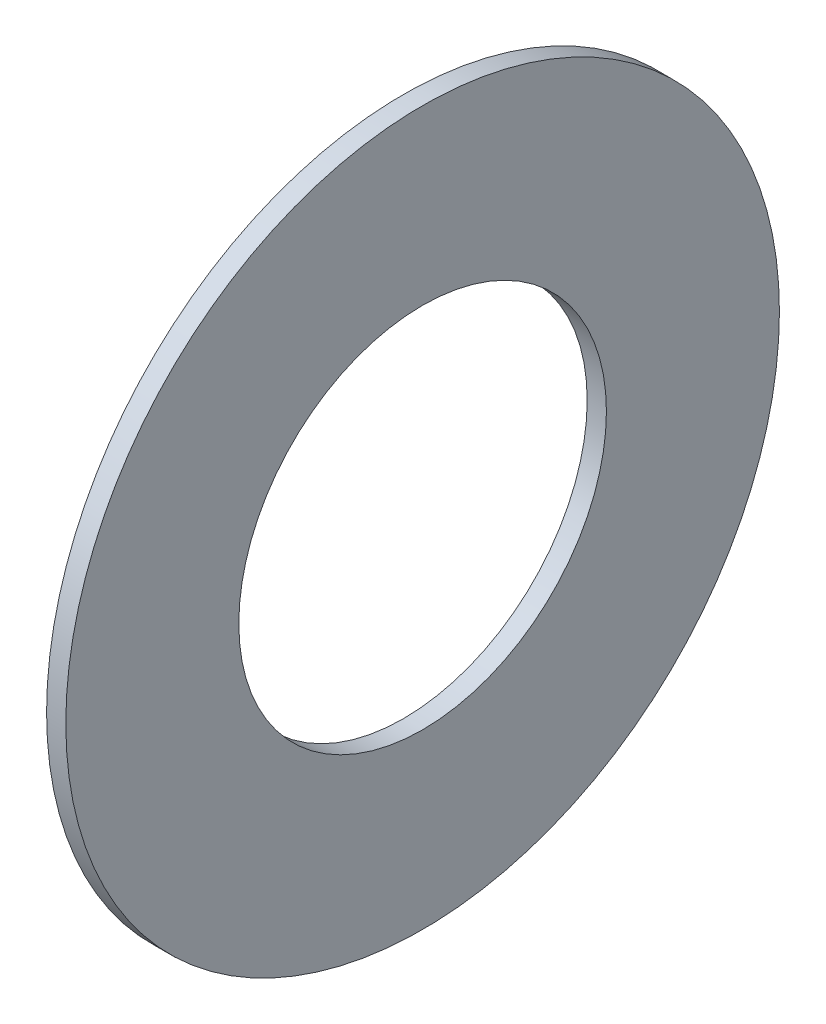
SolidWorks part; units mm, degrees
material "ﾎﾟﾘｵｷｼﾒﾁﾚﾝ(POM)ｱｾﾀｰﾙ共重合体"
ref_plane "正面" through (0, 0, 0) normal (0, 0, 1) x (1, 0, 0)
ref_plane "平面" through (0, 0, 0) normal (0, 1, 0) x (1, 0, 0)
ref_plane "右側面" through (0, 0, 0) normal (1, 0, 0) x (0, 0, -1)
sketch "ｽｹｯﾁ2" plane through (0, 0, 0) normal (0, 0, 1) x (1, 0, 0)
  line L0 (0, 0) -> (50000, 0) construction
  line L1 (-0.4, 14.85) -> (-0.4, 7.65)
  line L2 (-0.4, 7.65) -> (0.4, 7.65)
  line L3 (0.4, 7.65) -> (0.4, 14.85)
  line L4 (0.4, 14.85) -> (-0.4, 14.85)
  point P7 (0, 7.65)
  dimension "D1" = 0.8
  dimension "D2" = 15.3
  dimension "D3" = 29.7
revolve "回転1" add sketch "ｽｹｯﾁ2" angle 360 about L0
